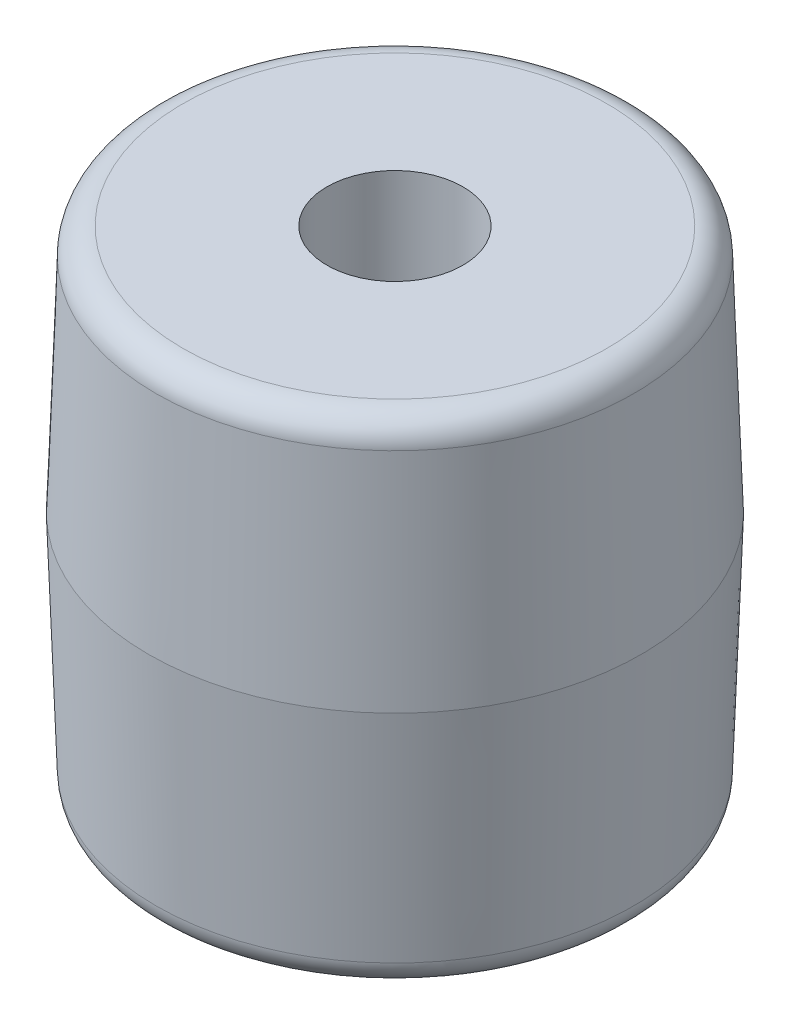
SolidWorks part; units mm, degrees
material "Natural Rubber"
ref_plane "Front Plane" through (0, 0, 0) normal (0, 0, 1) x (1, 0, 0)
ref_plane "Top Plane" through (0, 0, 0) normal (0, 1, 0) x (1, 0, 0)
ref_plane "Right Plane" through (0, 0, 0) normal (1, 0, 0) x (0, 0, -1)
sketch "Sketch1" plane through (0, 0, 0) normal (0, 1, 0) x (1, 0, 0)
  circle A0 centre (0, 0) radius 9.2075
  dimension "D1" = 18.415
extrude "Boss-Extrude1" add sketch "Sketch1" along normal blind 9.25 draft 2
mirror "Mirror1" about plane through (0, 0, 0) normal (0, 1, 0) of "Boss-Extrude1"
sketch "Sketch2" plane through (0, -9.25, 0) normal (0, -1, 0) x (-1, 0, 0)
  circle A0 centre (0, 0) radius 2.54
  dimension "D1" = 5.08
extrude "Cut-Extrude1" cut sketch "Sketch2" against normal through all
fillet "Fillet1" radius 1 2 edges at (0, -9.25, -8.8845) (0, 9.25, 8.8845)
